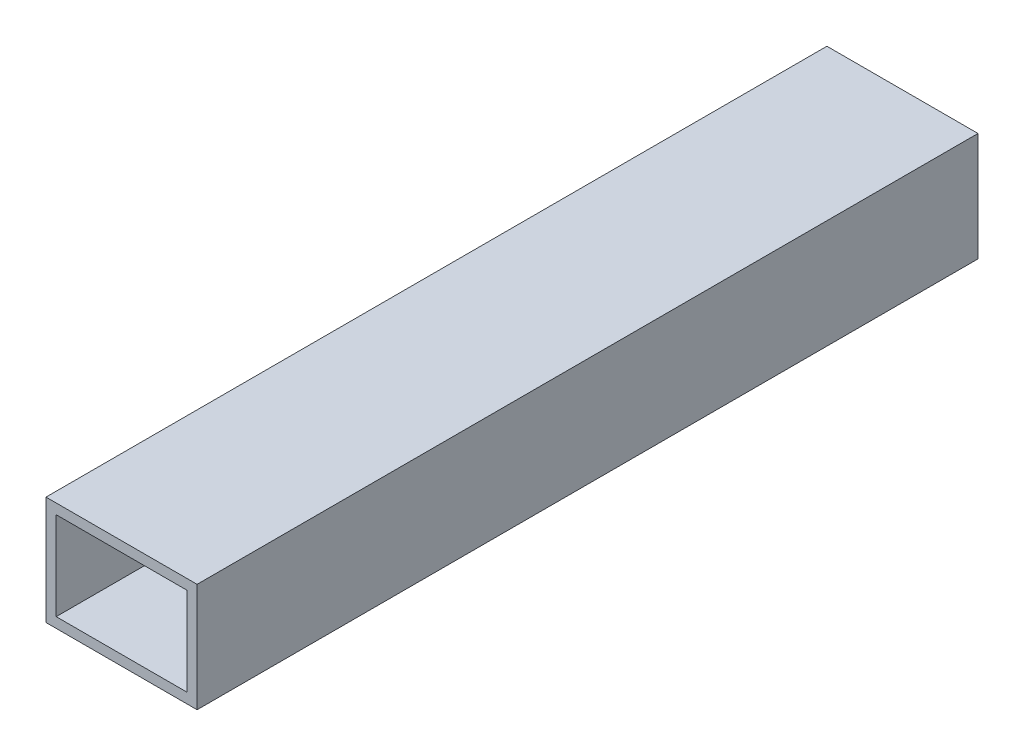
SolidWorks part; units mm, degrees
ref_plane "前视基准面" through (0, 0, 0) normal (0, 0, 1) x (1, 0, 0)
ref_plane "上视基准面" through (0, 0, 0) normal (0, 1, 0) x (1, 0, 0)
ref_plane "右视基准面" through (0, 0, 0) normal (1, 0, 0) x (0, 0, -1)
other "Configuration Table"
sketch "AICAD_SKETCH_F001" plane through (0, 0, 0) normal (0, 0, 1) x (1, 0, 0)
  line L0 (-8.9, -6.4) -> (8.9, -6.4)
  line L1 (8.9, -6.4) -> (8.9, 6.4)
  line L2 (8.9, 6.4) -> (-8.9, 6.4)
  line L3 (-8.9, 6.4) -> (-8.9, -6.4)
  point P0 (0, 0)
  dimension "D1" = 17.8
  dimension "D2" = 12.8
  dimension "D3" = 8.9
  dimension "D4" = 6.4
extrude "AICAD_F001_BASE_EXTRUDE" add sketch "AICAD_SKETCH_F001" along normal blind 92
sketch "AICAD_SKETCH_F002" plane through (0, 0, 92) normal (0, 0, 1) x (1, 0, 0)
  line L0 (-7.7, -5.2) -> (7.7, -5.2)
  line L1 (7.7, -5.2) -> (7.7, 5.2)
  line L2 (7.7, 5.2) -> (-7.7, 5.2)
  line L3 (-7.7, 5.2) -> (-7.7, -5.2)
  point P0 (0, 0)
  dimension "D1" = 15.4
  dimension "D2" = 10.4
  dimension "D3" = 7.7
  dimension "D4" = 5.2
extrude "AICAD_F002_CUT_EXTRUDE" cut sketch "AICAD_SKETCH_F002" against normal through all
